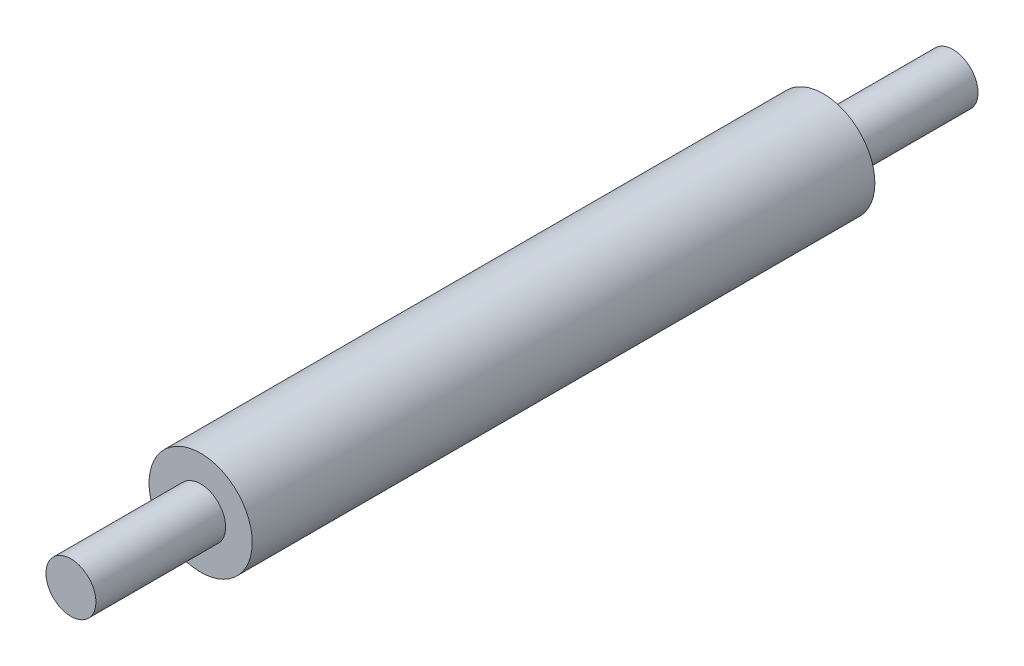
SolidWorks part; units mm, degrees
ref_plane "Front Plane" through (0, 0, 0) normal (0, 0, 1) x (1, 0, 0)
ref_plane "Top Plane" through (0, 0, 0) normal (0, 1, 0) x (1, 0, 0)
ref_plane "Right Plane" through (0, 0, 0) normal (1, 0, 0) x (0, 0, -1)
sketch "Sketch1" plane through (0, 0, 0) normal (0, 0, 1) x (1, 0, 0)
  circle A0 centre (0, 0) radius 7.95
  dimension "D1" = 15.9
extrude "Boss-Extrude1" add sketch "Sketch1" along normal mid plane 96
sketch "Sketch3" plane through (0, 0, 48) normal (0, 0, 1) x (1, 0, 0)
  circle A0 centre (0, 0) radius 3.85
  dimension "D1" = 7.7
extrude "Boss-Extrude2" add sketch "Sketch3" along normal blind 20
mirror "Mirror1" about plane through (0, 0, 0) normal (0, 0, 1) of "Boss-Extrude2"
